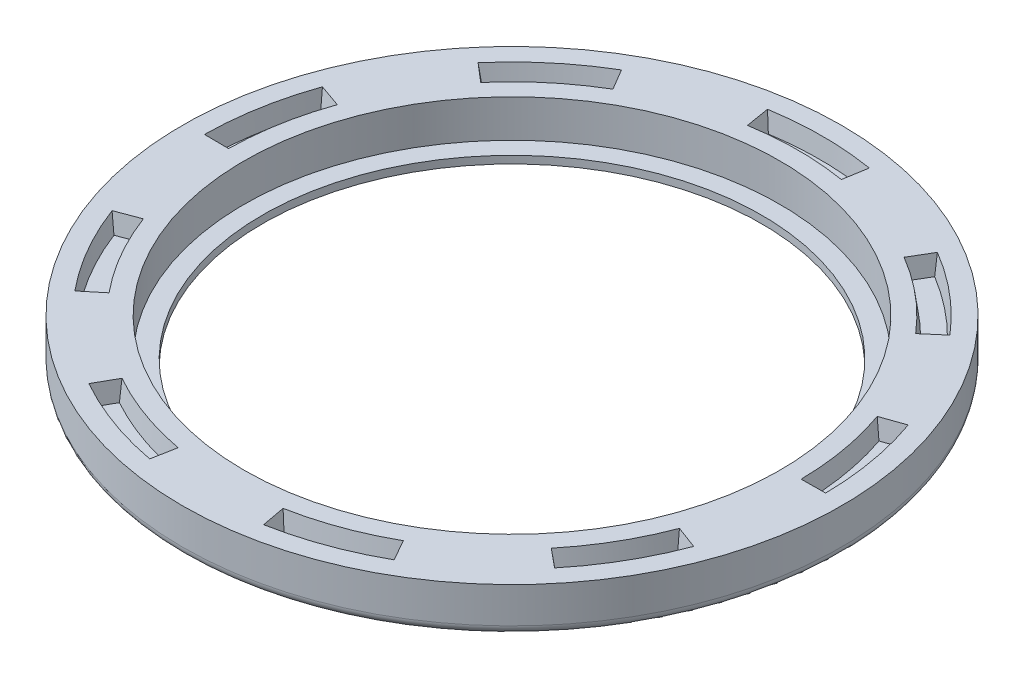
SolidWorks part; units mm, degrees
ref_plane "前视基准面" through (0, 0, 0) normal (0, 0, 1) x (1, 0, 0)
ref_plane "上视基准面" through (0, 0, 0) normal (0, 1, 0) x (1, 0, 0)
ref_plane "右视基准面" through (0, 0, 0) normal (1, 0, 0) x (0, 0, -1)
sketch "草图1" plane through (0, 0, 0) normal (0, 1, 0) x (1, 0, 0)
  circle A0 centre (0, 0) radius 17.5
  circle A1 centre (0, 0) radius 13
  dimension "D1" = 35
  dimension "D2" = 26
extrude "凸台-拉伸1" add sketch "草图1" along normal blind 2.4
sketch "草图2" plane through (0, 2.4, 0) normal (0, 1, 0) x (1, 0, 0)
  circle A0 centre (0, 0) radius 14.2276
extrude "切除-拉伸1" cut sketch "草图2" against normal blind 2
sketch "草图3" plane through (0, 0.4, 0) normal (0, 1, 0) x (1, 0, 0)
  circle A0 centre (0, 0) radius 13.25
  dimension "D1" = 26.5
extrude "切除-拉伸2" cut sketch "草图3" against normal blind 2
sketch "草图4" plane through (0, 2.4, 0) normal (0, 1, 0) x (1, 0, 0)
  line L0 (0, 0) -> (0, 18.8829) construction
  line L1 (-2.4913, 14.9964) -> (-2.7028, 16.2699)
  line L2 (2.4913, 14.9964) -> (2.7028, 16.2699)
  line L3 (7.7311, 13.0893) -> (8.3876, 14.2008)
  line L4 (11.5479, 9.8865) -> (12.5286, 10.7261)
  line L5 (14.336, 5.0575) -> (15.5534, 5.487)
  line L6 (15.2012, 0.1507) -> (16.492, 0.1635)
  line L7 (14.2329, -5.3407) -> (15.4415, -5.7942)
  line L8 (11.7416, -9.6557) -> (12.7387, -10.4757)
  line L9 (7.4701, -13.2399) -> (8.1045, -14.3643)
  line L10 (2.788, -14.9441) -> (3.0248, -16.2131)
  line L11 (-2.788, -14.9441) -> (-3.0248, -16.2131)
  line L12 (-7.4701, -13.2399) -> (-8.1045, -14.3643)
  line L13 (-11.7416, -9.6557) -> (-12.7387, -10.4757)
  line L14 (-14.2329, -5.3407) -> (-15.4415, -5.7942)
  line L15 (-15.2012, 0.1507) -> (-16.492, 0.1635)
  line L16 (-14.336, 5.0575) -> (-15.5534, 5.487)
  line L17 (-11.5479, 9.8865) -> (-12.5286, 10.7261)
  line L18 (-7.7311, 13.0893) -> (-8.3876, 14.2008)
  arc A0 (2.7028, 16.2699) -> (-2.7028, 16.2699) centre (0, 0) ccw
  arc A1 (2.4913, 14.9964) -> (-2.4913, 14.9964) centre (0, 0) ccw
  arc A2 (12.5286, 10.7261) -> (8.3876, 14.2008) centre (0, 0) ccw
  arc A3 (11.5479, 9.8865) -> (7.7311, 13.0893) centre (0, 0) ccw
  arc A4 (16.492, 0.1635) -> (15.5534, 5.487) centre (0, 0) ccw
  arc A5 (15.2012, 0.1507) -> (14.336, 5.0575) centre (0, 0) ccw
  arc A6 (12.7387, -10.4757) -> (15.4415, -5.7942) centre (0, 0) ccw
  arc A7 (11.7416, -9.6557) -> (14.2329, -5.3407) centre (0, 0) ccw
  arc A8 (3.0248, -16.2131) -> (8.1045, -14.3643) centre (0, 0) ccw
  arc A9 (2.788, -14.9441) -> (7.4701, -13.2399) centre (0, 0) ccw
  arc A10 (-8.1045, -14.3643) -> (-3.0248, -16.2131) centre (0, 0) ccw
  arc A11 (-7.4701, -13.2399) -> (-2.788, -14.9441) centre (0, 0) ccw
  arc A12 (-15.4415, -5.7942) -> (-12.7387, -10.4757) centre (0, 0) ccw
  arc A13 (-14.2329, -5.3407) -> (-11.7416, -9.6557) centre (0, 0) ccw
  arc A14 (-15.5534, 5.487) -> (-16.492, 0.1635) centre (0, 0) ccw
  arc A15 (-14.336, 5.0575) -> (-15.2012, 0.1507) centre (0, 0) ccw
  arc A16 (-8.3876, 14.2008) -> (-12.5286, 10.7261) centre (0, 0) ccw
  arc A17 (-7.7311, 13.0893) -> (-11.5479, 9.8865) centre (0, 0) ccw
  dimension "D1" = 9
extrude "切除-拉伸3" cut sketch "草图4" against normal blind 1 draft 8
fillet "圆角1" radius 0.5 1 edges at (0, 0, 17.5)
